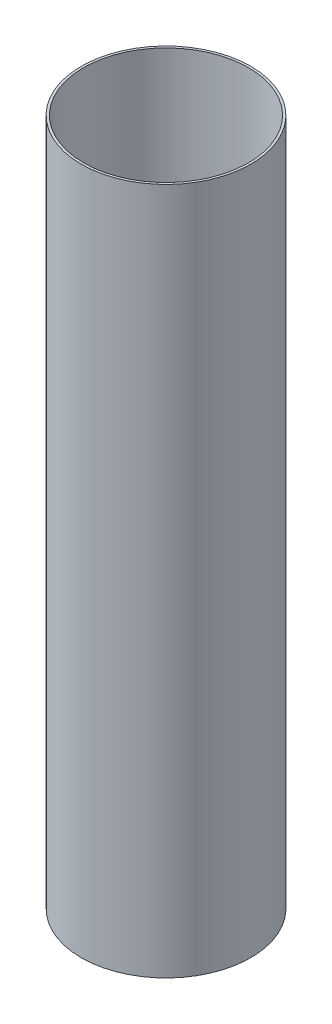
SolidWorks part; units mm, degrees
ref_plane "Front" through (0, 0, 0) normal (0, 0, 1) x (1, 0, 0)
ref_plane "Top" through (0, 0, 0) normal (0, 1, 0) x (1, 0, 0)
ref_plane "Right" through (0, 0, 0) normal (1, 0, 0) x (0, 0, -1)
sketch "Sketch1" plane through (0, 0, 0) normal (0, 1, 0) x (1, 0, 0)
  circle A0 centre (0, 0) radius 7.8359
  circle A1 centre (0, 0) radius 7.62
extrude "Boss-Extrude1" add sketch "Sketch1" along normal blind 63.5
